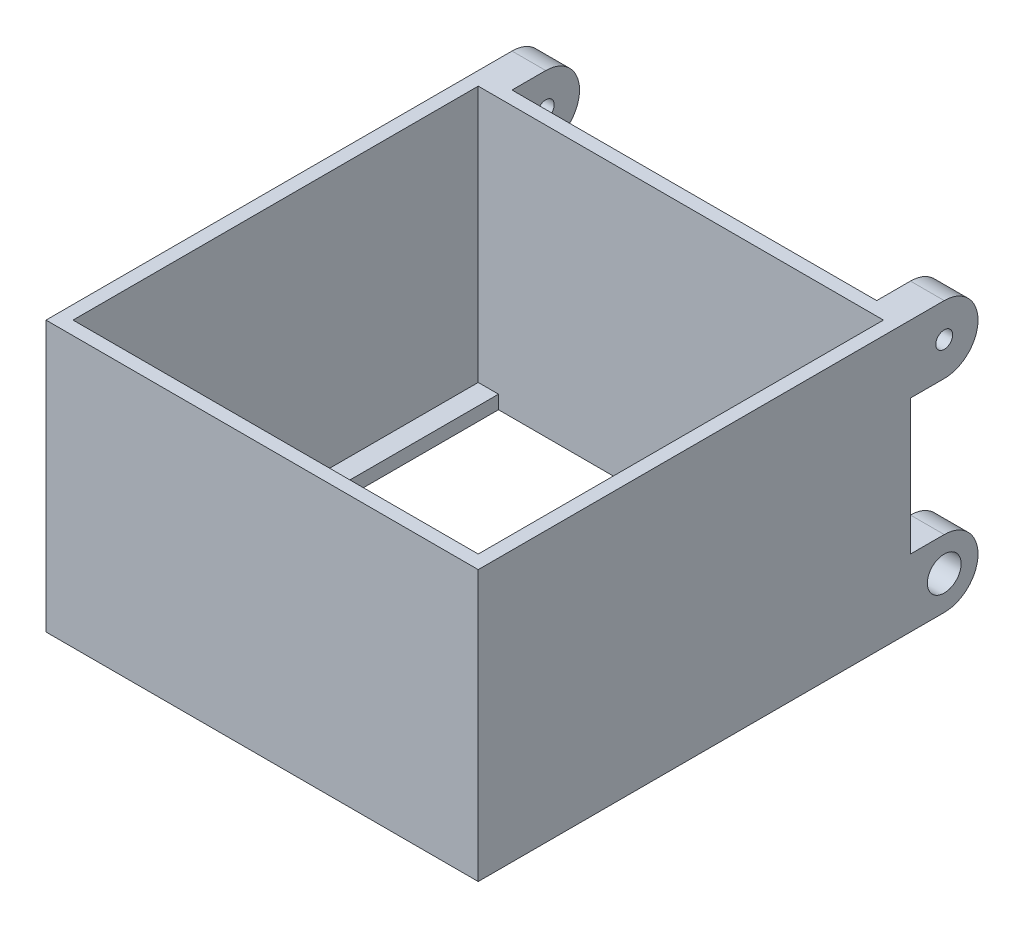
SolidWorks part; units mm, degrees
ref_plane "Front Plane" through (0, 0, 0) normal (0, 0, 1) x (1, 0, 0)
ref_plane "Top Plane" through (0, 0, 0) normal (0, 1, 0) x (1, 0, 0)
ref_plane "Right Plane" through (0, 0, 0) normal (1, 0, 0) x (0, 0, -1)
sketch "Sketch1" plane through (0, 0, 0) normal (0, 1, 0) x (1, 0, 0)
  line L0 (-40.64, 40.64) -> (40.64, 40.64)
  line L1 (-38.1, 38.1) -> (38.1, 38.1)
  line L2 (-38.1, 38.1) -> (-38.1, -38.1)
  line L3 (-38.1, -38.1) -> (38.1, -38.1)
  line L4 (38.1, 38.1) -> (38.1, -38.1)
  line L5 (40.64, 40.64) -> (40.64, -40.64)
  line L6 (-40.64, -40.64) -> (40.64, -40.64)
  line L7 (-40.64, 40.64) -> (-40.64, -40.64)
  point P4 (0, 38.1)
  point P6 (-38.1, 0)
  dimension "D1" = 76.2
  dimension "D2" = 76.2
  dimension "D3" = 2.54
extrude "Boss-Extrude1" add sketch "Sketch1" along normal blind 50.8
sketch "Sketch2" plane through (0, 0, 0) normal (0, 1, 0) x (1, 0, 0)
  line L0 (-38.1, -38.1) -> (38.1, -38.1) construction
  line L1 (-38.1, 38.1) -> (-34.29, 38.1)
  line L2 (-38.1, 38.1) -> (-38.1, -38.1)
  line L3 (-38.1, -38.1) -> (-34.29, -38.1)
  line L4 (-34.29, 38.1) -> (-34.29, -38.1)
  line L5 (0, 38.1) -> (0, -38.1) construction
  line L6 (38.1, 38.1) -> (-38.1, 38.1) construction
  line L7 (38.1, -38.1) -> (34.29, -38.1)
  line L8 (34.29, 38.1) -> (34.29, -38.1)
  line L9 (38.1, 38.1) -> (34.29, 38.1)
  line L10 (38.1, 38.1) -> (38.1, -38.1)
  dimension "D1" = 3.81
extrude "Boss-Extrude2" add sketch "Sketch2" along normal blind 2.54
fillet "Fillet1" [suppressed] radius 1.27
ref_plane "Plane1" through (0, 0, 0) normal (-1, 0, 0) x (0, 0, 1)
ref_plane "Plane2" through (0, 0, 0) normal (0, 0, 1) x (1, 0, 0)
ref_plane "Plane3" through (0, 25.4, 0) normal (0, -1, 0) x (-1, 0, 0)
sketch "Sketch3" plane through (40.64, 0, 0) normal (1, 0, 0) x (0, 0, -1)
  line L0 (46.99, 3.175) -> (46.99, 0) construction
  line L1 (46.99, 12.7) -> (40.64, 12.7)
  line L2 (46.99, 12.7) -> (46.99, 9.525) construction
  line L3 (46.99, 0) -> (40.64, 0)
  line L4 (40.64, 12.7) -> (40.64, 0)
  circle A0 centre (46.99, 6.35) radius 3.175
  arc A1 (46.99, 0) -> (46.99, 12.7) centre (46.99, 6.35) ccw
  dimension "D1" = 6.35
  dimension "D2" = 12.7
extrude "Boss-Extrude3" add sketch "Sketch3" against normal blind 6.35
sketch "Sketch4" plane through (40.64, 0, 0) normal (1, 0, 0) x (0, 0, -1)
  line L0 (46.99, 42.8625) -> (46.99, 38.1) construction
  line L1 (46.99, 50.8) -> (40.64, 50.8)
  line L2 (46.99, 50.8) -> (46.99, 46.0375) construction
  line L3 (46.99, 38.1) -> (40.64, 38.1)
  line L4 (40.64, 50.8) -> (40.64, 38.1)
  circle A0 centre (46.99, 44.45) radius 1.5875
  arc A1 (46.99, 38.1) -> (46.99, 50.8) centre (46.99, 44.45) ccw
  dimension "D1" = 3.175
  dimension "D2" = 6.35
extrude "Boss-Extrude4" add sketch "Sketch4" against normal blind 6.35
mirror "Mirror1" about plane through (0, 0, 0) normal (-1, 0, 0) of "Boss-Extrude4", "Boss-Extrude3"
